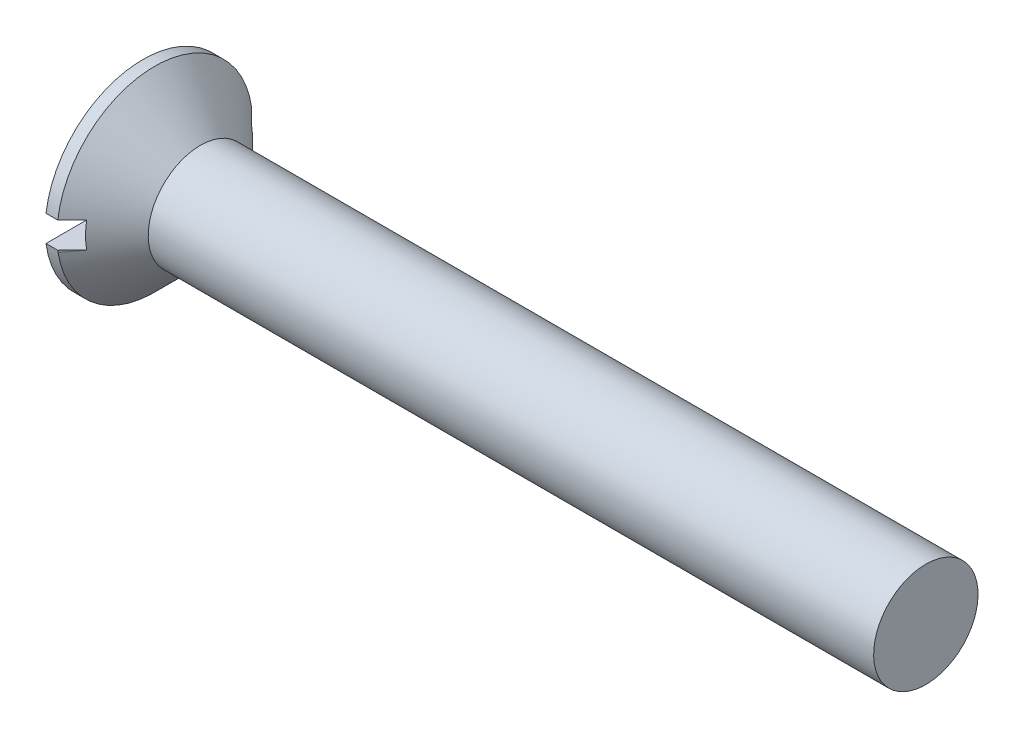
SolidWorks part; units mm, degrees
material "Plain Carbon Steel"
ref_plane "Front Plane" through (0, 0, 0) normal (0, 0, 1) x (1, 0, 0)
ref_plane "Top Plane" through (0, 0, 0) normal (0, 1, 0) x (1, 0, 0)
ref_plane "Right Plane" through (0, 0, 0) normal (1, 0, 0) x (0, 0, -1)
sketch "Sketch1" plane through (0, 0, 0) normal (0, 0, 1) x (1, 0, 0)
  line L0 (0, 0) -> (0, 3.75)
  line L1 (0, 3.75) -> (0.45, 3.75)
  line L2 (0.45, 3.75) -> (2.2, 2)
  line L3 (2.2, 2) -> (30, 2)
  line L4 (30, 2) -> (30, 0)
  line L5 (30, 0) -> (0, 0) construction
  line L6 (0, 0) -> (30, 0)
  dimension "D1" = 45
  dimension "D2" = 4
  dimension "D3" = 7.5
  dimension "D4" = 2.2
  dimension "D5" = 30
revolve "Revolve1" add sketch "Sketch1" angle 360 about L5
sketch "Sketch2" plane through (0, 0, 0) normal (-1, 0, 0) x (0, 0, 1)
  line L0 (3.75, 0) -> (-3.75, 0) construction
  line L1 (-3.75, 0.5) -> (3.75, 0.5)
  line L2 (-3.75, 0.5) -> (-3.75, -0.5)
  line L3 (-3.75, -0.5) -> (3.75, -0.5)
  line L4 (3.75, 0.5) -> (3.75, -0.5)
  circle A0 centre (0, 0) radius 3.75 construction
  dimension "D1" = 1
extrude "Cut-Extrude1" cut sketch "Sketch2" against normal blind 1
